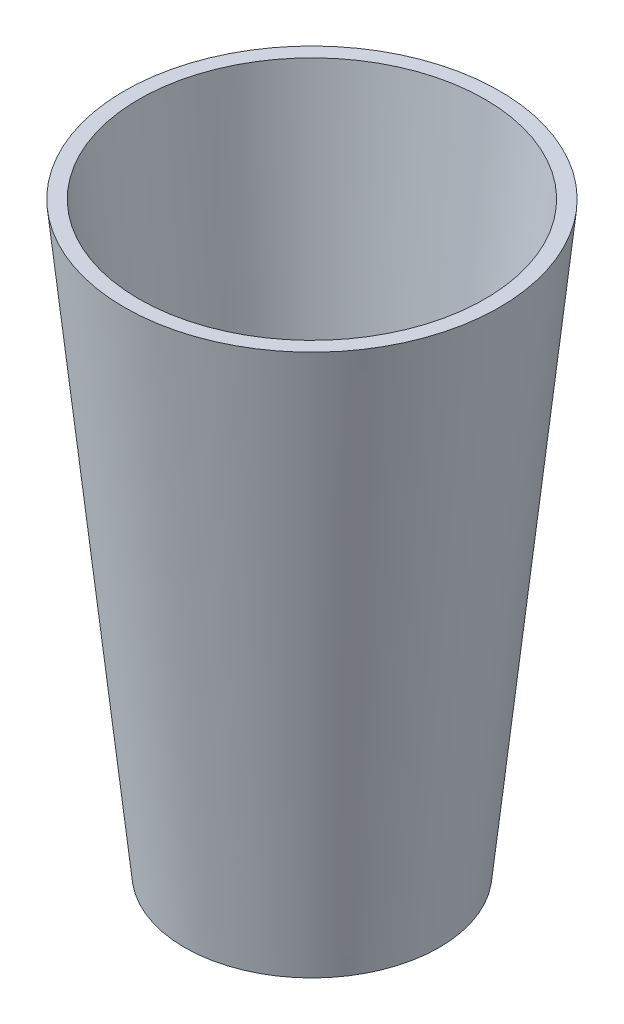
SolidWorks part; units mm, degrees
ref_plane "Plan de face" through (0, 0, 0) normal (0, 0, 1) x (1, 0, 0)
ref_plane "Plan de dessus" through (0, 0, 0) normal (0, 1, 0) x (1, 0, 0)
ref_plane "Plan de droite" through (0, 0, 0) normal (1, 0, 0) x (0, 0, -1)
sketch "Esquisse1" plane through (0, 0, 0) normal (0, 0, 1) x (1, 0, 0)
  line L0 (0, 50.1446) -> (0, -49.0071) construction
  line L1 (0, -41.803) -> (17.6312, -41.803)
  line L2 (17.6312, -41.803) -> (25.9728, 39.1488)
  line L3 (25.9728, 39.1488) -> (0, 39.1488)
  line L4 (0, 39.1488) -> (0, -41.803)
  dimension "D1" = 80.9518
  dimension "D2" = 25.9728
  dimension "D3" = 17.6312
  dimension "D4" = 41.803
  dimension "D5" = 99.1518
revolve "Révolution1" add sketch "Esquisse1" angle 360 about L0
shell "Coque4" thickness 2
